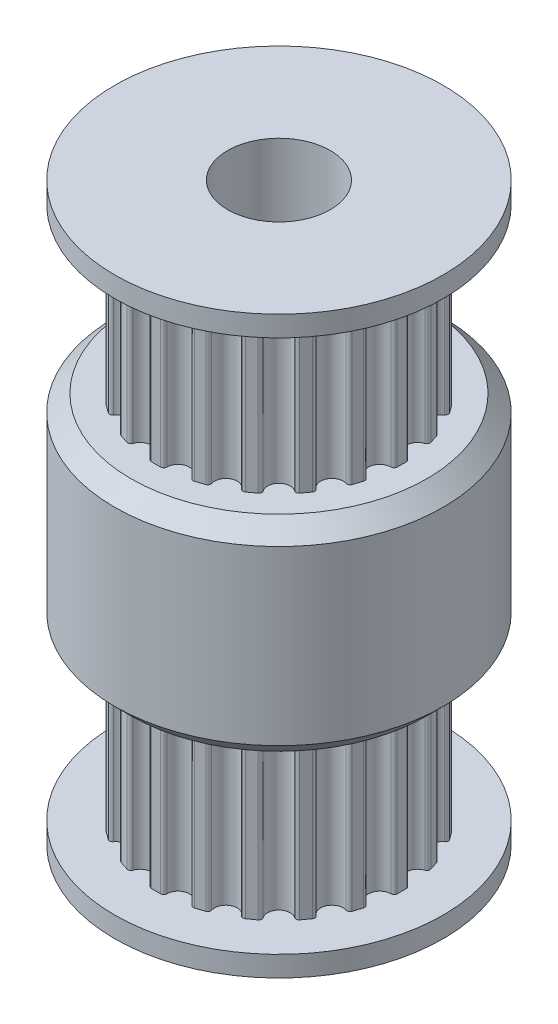
SolidWorks part; units mm, degrees
ref_plane "Front Plane" through (0, 0, 0) normal (0, 0, 1) x (1, 0, 0)
ref_plane "Top Plane" through (0, 0, 0) normal (0, 1, 0) x (1, 0, 0)
ref_plane "Right Plane" through (0, 0, 0) normal (1, 0, 0) x (0, 0, -1)
sketch "Sketch1" plane through (0, 0, 0) normal (0, 1, 0) x (1, 0, 0)
  circle A0 centre (0, 0) radius 8
  dimension "D1" = 16
extrude "Boss-Extrude1" add sketch "Sketch1" along normal mid plane 10 contours A0
chamfer "Chamfer1" distance 0.8 angle 45 2 edges at (0, 5, 8) (0, -5, 8)
sketch "Sketch9" plane through (0, -5, 0) normal (0, -1, 0) x (1, 0, 0)
  circle A0 centre (0, 0) radius 6.365
  dimension "D1" = 12.73
extrude "Boss-Extrude2" add sketch "Sketch9" along normal blind 8
sketch "Sketch10" plane through (0, -13, 0) normal (0, -1, 0) x (1, 0, 0)
  line L0 (0, 0) -> (0, 6.365) construction
  line L1 (0, 5.985) -> (0.2242, 5.985)
  line L2 (0, 5.985) -> (0, 6.365)
  line L3 (0, 0) -> (0.9242, 5.835) construction
  line L5 (1.8495, 5.6921) -> (1.6363, 5.7613)
  line L6 (1.8495, 5.6921) -> (1.9669, 6.0535)
  line L8 (1.0801, 6.3149) -> (0.9242, 6.3396)
  line L9 (0.9242, 6.3396) -> (0, 6.3777)
  line L10 (0, 6.3777) -> (0, 6.365)
  line L11 (1.0801, 6.3149) -> (1.9669, 6.0744)
  line L12 (1.9669, 6.0744) -> (1.9669, 6.0535)
  circle A0 centre (0, 0) radius 6.365 construction
  arc A1 (0.2242, 5.985) -> (0.3742, 5.835) centre (0.2242, 5.835) cw
  arc A2 (0.3742, 5.835) -> (1.4473, 5.665) centre (0.9242, 5.835) ccw
  arc A3 (1.6363, 5.7613) -> (1.4473, 5.665) centre (1.5899, 5.6187) ccw
  dimension "D3" = 0.38
  dimension "D1" = 0.15
  dimension "D2" = 0.55
extrude "Cut-Extrude6" cut sketch "Sketch10" against normal blind 8
pattern_circular "CirPattern1" count 20 over 360 about axis through (0, 0, 0) along (0, 1, 0) of "Cut-Extrude6"
sketch "Sketch11" plane through (0, 5, 0) normal (0, 1, 0) x (1, 0, 0)
  circle A0 centre (0, 0) radius 6.365
  dimension "D1" = 12.73
extrude "Boss-Extrude3" add sketch "Sketch11" along normal blind 8
mirror "Mirror2" about plane through (0, 0, 0) normal (0, 1, 0) of "CirPattern1", "Cut-Extrude6"
sketch "Sketch14" plane through (0, 13, 0) normal (0, 1, 0) x (1, 0, 0)
  circle A0 centre (0, 0) radius 8
extrude "Boss-Extrude4" add sketch "Sketch14" along normal blind 1
mirror "Mirror3" about plane through (0, 0, 0) normal (0, 1, 0) of "Boss-Extrude4"
sketch "Sketch15" plane through (0, 14, 0) normal (0, 1, 0) x (1, 0, 0)
  circle A0 centre (0, 0) radius 2.5
extrude "Cut-Extrude7" cut sketch "Sketch15" against normal through all
equation "\"n\"= 20"
equation "\"p\"= 2"
equation "\"pd\"= \"n\" * \"p\" / pi"
